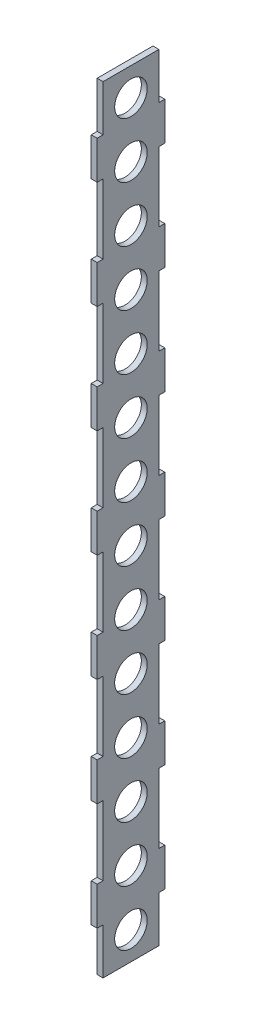
SolidWorks part; units mm, degrees
ref_plane "Plan de face" through (0, 0, 0) normal (0, 0, 1) x (1, 0, 0)
ref_plane "Plan de dessus" through (0, 0, 0) normal (0, 1, 0) x (1, 0, 0)
ref_plane "Plan de droite" through (0, 0, 0) normal (1, 0, 0) x (0, 0, -1)
sketch "Esquisse1" plane through (0, 0, 0) normal (0, 0, 1) x (1, 0, 0)
  line L0 (-56, 163.6) -> (-56, 163.346)
  line L1 (-52.825, 163.6) -> (-52.825, 163.346)
  line L2 (-56, 183.6) -> (-56, 183.854)
  line L3 (-52.825, 183.6) -> (-52.825, 183.854)
  line L8 (-52.571, 183.854) -> (-56.254, 183.854) construction
  line L9 (-56.254, 163.346) -> (-52.571, 163.346) construction
  line L10 (-56, 125.7333) -> (-56, 125.9873)
  line L11 (-52.825, 125.7333) -> (-52.825, 125.9873)
  line L12 (-56, 105.7333) -> (-56, 105.4793)
  line L13 (-52.825, 105.7333) -> (-52.825, 105.4793)
  line L14 (-52.571, 125.9873) -> (-56.254, 125.9873) construction
  line L15 (-56.254, 105.4793) -> (-52.571, 105.4793) construction
  line L16 (-56, 67.8667) -> (-56, 68.1207)
  line L17 (-52.825, 67.8667) -> (-52.825, 68.1207)
  line L18 (-52.825, 47.8667) -> (-52.825, 47.6127)
  line L19 (-56, 47.8667) -> (-56, 47.6127)
  line L20 (-56.254, 47.6127) -> (-52.571, 47.6127) construction
  line L21 (-52.571, 68.1207) -> (-56.254, 68.1207) construction
  line L22 (-56, 10) -> (-56, 10.254)
  line L23 (-52.825, 10) -> (-52.825, 10.254)
  line L24 (-56, -10) -> (-56, -10.254)
  line L25 (-52.825, -10) -> (-52.825, -10.254)
  line L26 (-56.254, -10.254) -> (-52.571, -10.254) construction
  line L27 (-52.571, 10.254) -> (-56.254, 10.254) construction
  line L92 (-56, -183.6) -> (-52.825, -183.6) construction
  line L93 (-56, -163.6) -> (-56, -183.6) construction
  line L94 (-52.825, -183.6) -> (-52.825, -163.6) construction
  line L95 (-52.825, -163.6) -> (-56, -163.6) construction
  line L96 (-56, -125.7333) -> (-52.825, -125.7333) construction
  line L97 (-56, -105.7333) -> (-56, -125.7333) construction
  line L98 (-52.825, -125.7333) -> (-52.825, -105.7333) construction
  line L99 (-52.825, -105.7333) -> (-56, -105.7333) construction
  line L100 (-56, -67.8667) -> (-52.825, -67.8667) construction
  line L101 (-56, -47.8667) -> (-56, -67.8667) construction
  line L102 (-52.825, -67.8667) -> (-52.825, -47.8667) construction
  line L103 (-52.825, -47.8667) -> (-56, -47.8667) construction
  line L104 (-56, -10) -> (-52.825, -10) construction
  line L105 (-52.825, 10) -> (-56, 10) construction
  line L106 (-56, 10) -> (-56, -10) construction
  line L107 (-52.825, -10) -> (-52.825, 10) construction
  line L108 (-56, 47.8667) -> (-52.825, 47.8667) construction
  line L109 (-56, 67.8667) -> (-56, 47.8667) construction
  line L110 (-52.825, 47.8667) -> (-52.825, 67.8667) construction
  line L111 (-52.825, 67.8667) -> (-56, 67.8667) construction
  line L112 (-56, 105.7333) -> (-52.825, 105.7333) construction
  line L113 (-52.825, 105.7333) -> (-52.825, 125.7333) construction
  line L114 (-56, 125.7333) -> (-56, 105.7333) construction
  line L115 (-52.825, 125.7333) -> (-56, 125.7333) construction
  line L116 (-56, 163.6) -> (-52.825, 163.6) construction
  line L117 (-52.825, 183.6) -> (-56, 183.6) construction
  line L118 (-52.825, 163.6) -> (-52.825, 183.6) construction
  line L119 (-56, 183.6) -> (-56, 163.6) construction
  line L120 (-56, -183.6) -> (-52.825, -183.6) construction
  line L121 (-56, -163.6) -> (-56, -183.6)
  line L122 (-52.825, -183.6) -> (-52.825, -163.6)
  line L123 (-52.825, -163.6) -> (-56, -163.6) construction
  line L124 (-56, -125.7333) -> (-52.825, -125.7333) construction
  line L125 (-56, -105.7333) -> (-56, -125.7333)
  line L126 (-52.825, -125.7333) -> (-52.825, -105.7333)
  line L127 (-52.825, -105.7333) -> (-56, -105.7333) construction
  line L128 (-56, -67.8667) -> (-52.825, -67.8667) construction
  line L129 (-56, -47.8667) -> (-56, -67.8667)
  line L130 (-52.825, -67.8667) -> (-52.825, -47.8667)
  line L131 (-52.825, -47.8667) -> (-56, -47.8667) construction
  line L132 (-56, -10) -> (-52.825, -10) construction
  line L133 (-52.825, 10) -> (-56, 10) construction
  line L134 (-56, 10) -> (-56, -10)
  line L135 (-52.825, -10) -> (-52.825, 10)
  line L136 (-56, 47.8667) -> (-52.825, 47.8667) construction
  line L137 (-56, 67.8667) -> (-56, 47.8667)
  line L138 (-52.825, 47.8667) -> (-52.825, 67.8667)
  line L139 (-52.825, 67.8667) -> (-56, 67.8667) construction
  line L140 (-56, 105.7333) -> (-52.825, 105.7333) construction
  line L141 (-52.825, 105.7333) -> (-52.825, 125.7333)
  line L142 (-56, 125.7333) -> (-56, 105.7333)
  line L143 (-52.825, 125.7333) -> (-56, 125.7333) construction
  line L144 (-56, 163.6) -> (-52.825, 163.6) construction
  line L145 (-52.825, 183.6) -> (-56, 183.6) construction
  line L146 (-52.825, 163.6) -> (-52.825, 183.6)
  line L147 (-56, 183.6) -> (-56, 163.6)
  line L148 (-56, -183.854) -> (-52.825, -183.854)
  line L150 (-52.825, -163.346) -> (-56, -163.346)
  line L152 (-56, -125.9873) -> (-52.825, -125.9873)
  line L154 (-52.825, -105.4793) -> (-56, -105.4793)
  line L156 (-56, -68.1207) -> (-52.825, -68.1207)
  line L158 (-52.825, -47.6127) -> (-56, -47.6127)
  line L160 (-56, -10.254) -> (-52.825, -10.254)
  line L162 (-52.825, 10.254) -> (-56, 10.254)
  line L164 (-56, 47.6127) -> (-52.825, 47.6127)
  line L166 (-52.825, 68.1207) -> (-56, 68.1207)
  line L168 (-56, 105.4793) -> (-52.825, 105.4793)
  line L170 (-52.825, 125.9873) -> (-56, 125.9873)
  line L172 (-56, 163.346) -> (-52.825, 163.346)
  line L174 (-52.825, 183.854) -> (-56, 183.854)
  line L176 (-56.254, 183.854) -> (-56.254, 163.346) construction
  line L177 (-52.571, 163.346) -> (-52.571, 183.854) construction
  line L178 (-56.254, 125.9873) -> (-56.254, 105.4793) construction
  line L179 (-52.571, 105.4793) -> (-52.571, 125.9873) construction
  line L180 (-56.254, 68.1207) -> (-56.254, 47.6127) construction
  line L181 (-52.571, 47.6127) -> (-52.571, 68.1207) construction
  line L182 (-56.254, 10.254) -> (-56.254, -10.254) construction
  line L183 (-52.571, -10.254) -> (-52.571, 10.254) construction
  line L184 (-56, -47.8667) -> (-56, -47.6127)
  line L185 (-52.825, -47.8667) -> (-52.825, -47.6127)
  line L186 (-56, -67.8667) -> (-56, -68.1207)
  line L187 (-52.825, -67.8667) -> (-52.825, -68.1207)
  line L188 (-56.254, -68.1207) -> (-52.571, -68.1207) construction
  line L189 (-56.254, -47.6127) -> (-56.254, -68.1207) construction
  line L190 (-52.571, -68.1207) -> (-52.571, -47.6127) construction
  line L191 (-52.571, -47.6127) -> (-56.254, -47.6127) construction
  line L192 (-56, -105.7333) -> (-56, -105.4793)
  line L193 (-52.825, -105.7333) -> (-52.825, -105.4793)
  line L194 (-56, -125.7333) -> (-56, -125.9873)
  line L195 (-52.825, -125.7333) -> (-52.825, -125.9873)
  line L196 (-56.254, -125.9873) -> (-52.571, -125.9873) construction
  line L197 (-56.254, -105.4793) -> (-56.254, -125.9873) construction
  line L198 (-52.571, -125.9873) -> (-52.571, -105.4793) construction
  line L199 (-52.571, -105.4793) -> (-56.254, -105.4793) construction
  line L200 (-56, -183.6) -> (-56, -183.854)
  line L201 (-52.825, -183.6) -> (-52.825, -183.854)
  line L202 (-56, -163.6) -> (-56, -163.346)
  line L203 (-52.825, -163.6) -> (-52.825, -163.346)
  line L204 (-52.571, -163.346) -> (-56.254, -163.346) construction
  line L205 (-56.254, -163.346) -> (-56.254, -183.854) construction
  line L206 (-52.571, -183.854) -> (-52.571, -163.346) construction
  line L207 (-56.254, -183.854) -> (-52.571, -183.854) construction
  dimension "D1" = 0.254
extrude "Boss.-Extru.1" add sketch "Esquisse1" along normal blind 33.175 and the other way up to surface (3.175 mm away)
sketch "Esquisse2" plane through (0, -10.254, 0) normal (0, -1, 0) x (1, 0, 0)
  line L1 (-56, 30) -> (-52.825, 30)
  line L2 (-56, 30) -> (-56, 0)
  line L3 (-56, 0) -> (-52.825, 0)
  line L4 (-52.825, 30) -> (-52.825, 0)
  line L6 (-56, 33.175) -> (-52.825, 33.175) construction
  line L7 (-100, 0) -> (100, 0) construction
  line L8 (-56, -3.175) -> (-56, 33.175) construction
  line L9 (-52.825, -3.175) -> (-52.825, 33.175) construction
  dimension "D1" = 3.175
extrude "Boss.-Extru.2" add sketch "Esquisse2" along normal up to surface (198.346 mm away) and the other way up to surface (218.854 mm away)
ref_plane "Plan1" through (0, 0, 15) normal (0, 0, 1) x (1, 0, 0)
sketch "Sketch1" plane through (-52.825, 0, 0) normal (1, 0, 0) x (0, 0, -1)
  line L0 (-15, 1.7463) -> (-15, -1.7463) construction
  line L1 (-30, -208.6) -> (0, -208.6) construction
  circle A0 centre (-15, -193.6) radius 8.75
  dimension "D1" = 17.5
  dimension "D2" = 15
extrude "Cut-Extrude1" cut sketch "Sketch1" against normal up to next
pattern_linear "LPattern1" count 14 spacing 29.785 along (0, 1, 0) of "Cut-Extrude1"
equation "\"D1@Esquisse2\"=\"EpaisseurBois@corps_bottom-1.Part\""
